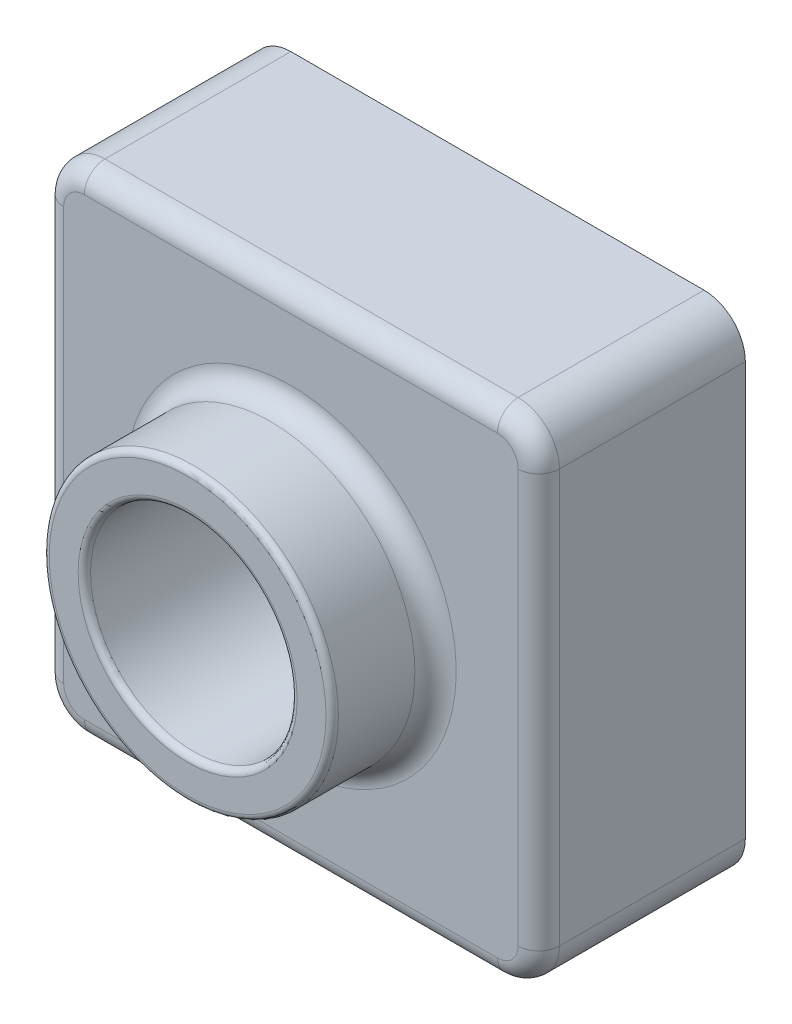
SolidWorks part; units mm, degrees
ref_plane "Front Plane" through (0, 0, 0) normal (0, 0, 1) x (1, 0, 0)
ref_plane "Top Plane" through (0, 0, 0) normal (0, 1, 0) x (1, 0, 0)
ref_plane "Right Plane" through (0, 0, 0) normal (1, 0, 0) x (0, 0, -1)
other "Configuration Table"
sketch "Sketch2" plane through (0, 0, 0) normal (0, 0, 1) x (1, 0, 0)
  line L1 (0, 0) -> (120, 0)
  line L2 (0, 0) -> (0, 120)
  line L3 (0, 120) -> (120, 120)
  line L4 (120, 0) -> (120, 120)
  dimension "D1" = 120
  dimension "D2" = 120
extrude "Boss-Extrude1" add sketch "Sketch2" along normal blind 50
sketch "Sketch4" plane through (0, 0, 50) normal (0, 0, 1) x (1, 0, 0)
  line L0 (120, 120) -> (0, 120) construction
  line L1 (0, 120) -> (0, 0) construction
  circle A0 centre (60, 60) radius 35
  dimension "D1" = 60
  dimension "D3" = 70
  dimension "D2" = 60
extrude "Boss-Extrude2" add sketch "Sketch4" along normal blind 25
sketch "Sketch6" plane through (0, 0, 75) normal (0, 0, 1) x (1, 0, 0)
  circle A0 centre (60, 60) radius 25
  dimension "D1" = 50
extrude "Cut-Extrude1" cut sketch "Sketch6" against normal through all
fillet "Fillet1" radius 10 4 edges at (0, 0, 25) (120, 0, 25) (120, 120, 25) (0, 120, 25)
fillet "Fillet2" radius 1.5 2 edges at (95, 60, 75) (85, 60, 75)
fillet "Fillet3" radius 5 9 edges at (25, 60, 50) (2.9289, 117.0711, 50) (60, 120, 50) (117.0711, 117.0711, 50) (120, 60, 50) (117.0711, 2.9289, 50) (60, 0, 50) (2.9289, 2.9289, 50) (0, 60, 50)
shell "Shell1" thickness 2
